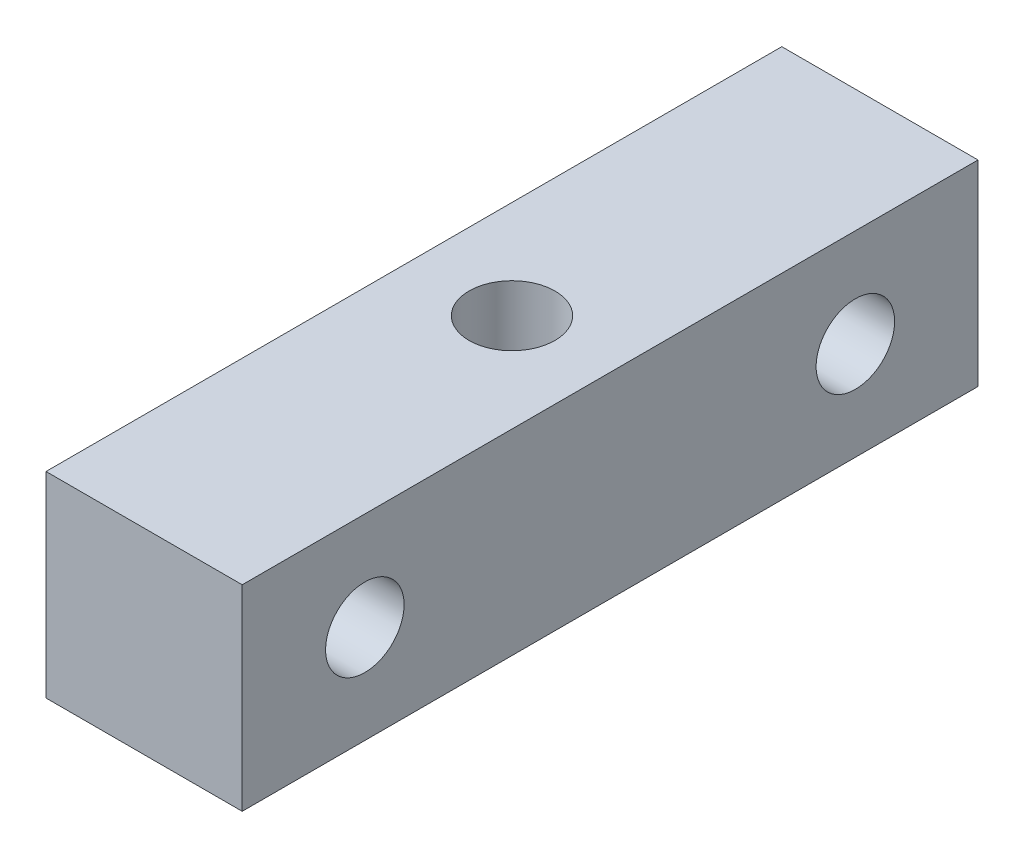
SolidWorks part; units mm, degrees
material "玻纤增强尼龙1010"
ref_plane "前视基准面" through (0, 0, 0) normal (0, 0, 1) x (1, 0, 0)
ref_plane "上视基准面" through (0, 0, 0) normal (0, 1, 0) x (1, 0, 0)
ref_plane "右视基准面" through (0, 0, 0) normal (1, 0, 0) x (0, 0, -1)
sketch "草图2" plane through (0, 0, 0) normal (0, 0, 1) x (1, 0, 0)
  line L1 (-4, -4) -> (4, -4)
  line L2 (-4, -4) -> (-4, 4)
  line L3 (-4, 4) -> (4, 4)
  line L4 (4, -4) -> (4, 4)
  line L5 (-4, -4) -> (4, 4) construction
  line L6 (-4, 4) -> (4, -4) construction
  point P0 (0, 0)
  dimension "D1" = 8
  dimension "D2" = 8
extrude "凸台-拉伸1" add sketch "草图2" along normal blind 30
sketch "草图3" plane through (0, 4, 0) normal (0, 1, 0) x (1, 0, 0)
  line L0 (0, 0) -> (0, -30) construction
  line L1 (4, -30) -> (-4, -30) construction
  circle A0 centre (0, -15) radius 1.75
  dimension "D1" = 3.5
extrude "切除-拉伸1" cut sketch "草图3" against normal through all
sketch "草图4" plane through (4, 0, 0) normal (1, 0, 0) x (0, 0, -1)
  line L0 (0, 0) -> (-30, 0) construction
  line L1 (-30, -4) -> (-30, 4) construction
  circle A0 centre (-25, 0) radius 1.6
  circle A1 centre (-5, 0) radius 1.6
  dimension "D1" = 3.2
  dimension "D2" = 5
  dimension "D3" = 5
extrude "切除-拉伸2" cut sketch "草图4" against normal through all
